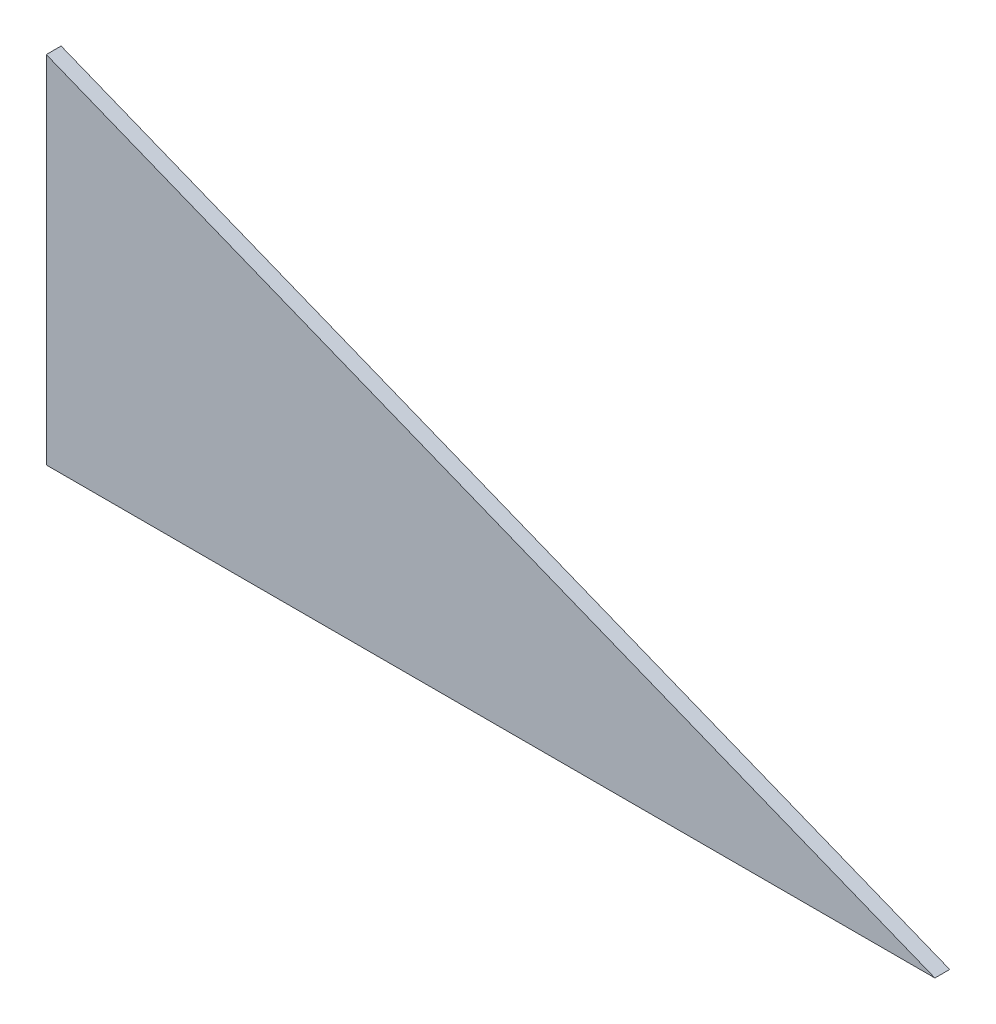
SolidWorks part; units mm, degrees
ref_plane "Front Plane" through (0, 0, 0) normal (0, 0, 1) x (1, 0, 0)
ref_plane "Top Plane" through (0, 0, 0) normal (0, 1, 0) x (1, 0, 0)
ref_plane "Right Plane" through (0, 0, 0) normal (1, 0, 0) x (0, 0, -1)
sketch "Sketch1" plane through (0, 0, 0) normal (0, 0, 1) x (1, 0, 0)
  line L0 (0, 76.2) -> (0, 0)
  line L1 (0, 0) -> (190.5, 0)
  line L3 (0, 76.2) -> (190.5, 0)
  point P5 (0, 0)
  point P6 (235.1415, 0)
  point P7 (193.594, 0)
  dimension "D1" = 190.5
  dimension "D2" = 76.2
extrude "Boss-Extrude1" add sketch "Sketch1" along normal blind 3.175
